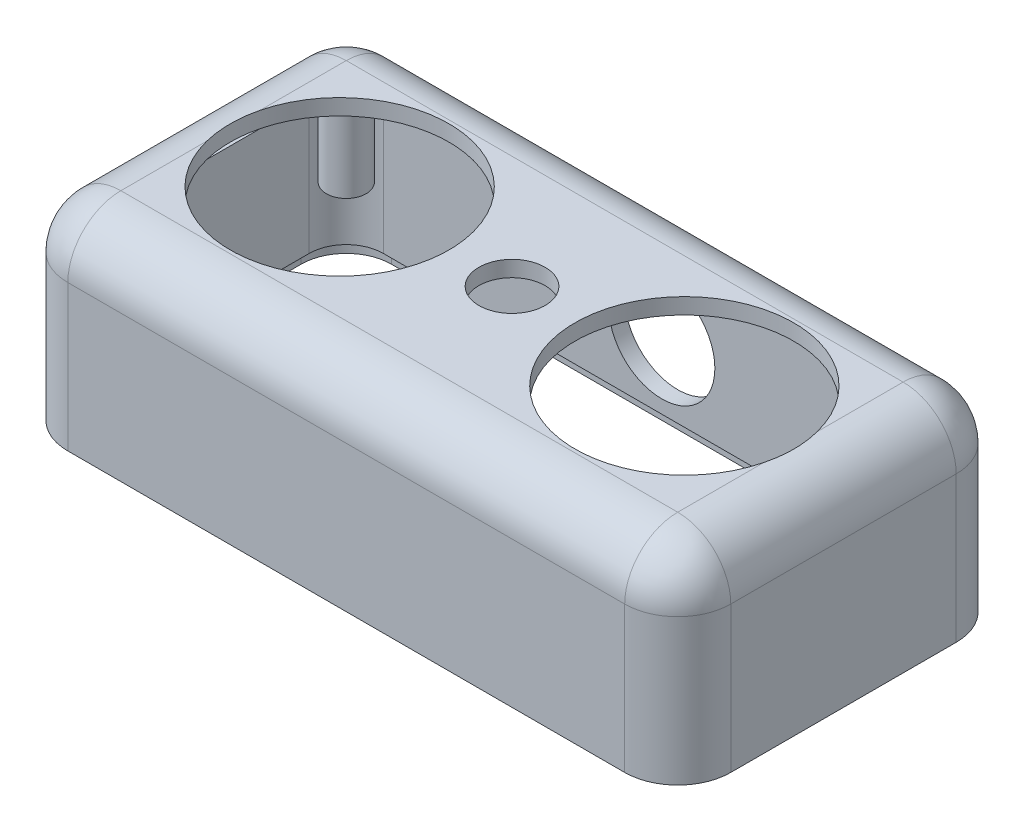
SolidWorks part; units mm, degrees
ref_plane "Front Plane" through (0, 0, 0) normal (0, 0, 1) x (1, 0, 0)
ref_plane "Top Plane" through (0, 0, 0) normal (0, 1, 0) x (1, 0, 0)
ref_plane "Right Plane" through (0, 0, 0) normal (1, 0, 0) x (0, 0, -1)
sketch "Sketch1" plane through (0, 0, 0) normal (0, 1, 0) x (1, 0, 0)
  line L1 (0, 0) -> (50, 0)
  line L2 (0, 0) -> (0, 25)
  line L3 (0, 25) -> (50, 25)
  line L4 (50, 0) -> (50, 25)
  dimension "D1" = 50
  dimension "D2" = 25
extrude "Boss-Extrude2" add sketch "Sketch1" along normal blind 15
fillet "Fillet1" radius 4 4 edges at (50, 7.5, 0) (0, 7.5, 0) (0, 7.5, -25) (50, 7.5, -25)
fillet "Fillet2" radius 4 8 edges at (1.1716, 15, -1.1716) (0, 15, -12.5) (1.1716, 15, -23.8284) (25, 15, -25) (48.8284, 15, -23.8284) (50, 15, -12.5) (48.8284, 15, -1.1716) (25, 15, 0)
shell "Shell1" thickness 1.2
sketch "Sketch2" plane through (0, 13.8, 0) normal (0, -1, 0) x (1, 0, 0)
  line L0 (4, -21) -> (4, -4) construction
  line L1 (38, -12.5) -> (12, -12.5) construction
  line L3 (46, -21) -> (4, -21) construction
  circle A0 centre (38, -12.5) radius 8.25
  circle A1 centre (12, -12.5) radius 8.25
  point P4 (25, -12.5)
  point P9 (4, -12.5)
  point P10 (25, -21)
  dimension "D2" = 16.5
  dimension "D1" = 26
extrude "Cut-Extrude1" cut sketch "Sketch2" against normal through all
sketch "Sketch3" plane through (0, 13.8, 0) normal (0, -1, 0) x (1, 0, 0)
  line L0 (46.25, -21.25) -> (3.75, -21.25) construction
  line L1 (3.75, -21.25) -> (3.75, -3.75) construction
  line L2 (3.75, -3.75) -> (46.25, -3.75) construction
  line L3 (46.25, -3.75) -> (46.25, -21.25) construction
  line L5 (38, -12.5) -> (12, -12.5) construction
  circle A0 centre (46.25, -21.25) radius 1.5
  circle A1 centre (3.75, -21.25) radius 1.5
  circle A2 centre (3.75, -3.75) radius 1.5
  circle A3 centre (46.25, -3.75) radius 1.5
  circle A4 centre (38, -12.5) radius 8.25 construction
  circle A5 centre (38, -12.5) radius 8.25
  circle A6 centre (12, -12.5) radius 8.25 construction
  circle A7 centre (12, -12.5) radius 8.25
  point P14 (25, -21.25)
  point P15 (25, -12.5)
  point P16 (3.75, -12.5)
  dimension "D1" = 3
  dimension "D2" = 42.5
  dimension "D3" = 17.5
extrude "Boss-Extrude3" add sketch "Sketch3" along normal blind 7 contours A1 | A2 | A3 | A0
sketch "Sketch6" plane through (0, 6.8, 0) normal (0, -1, 0) x (1, 0, 0)
  circle A0 centre (46.25, -3.75) radius 0.5
  circle A1 centre (46.25, -21.25) radius 0.5
  circle A2 centre (3.75, -21.25) radius 0.5
  circle A3 centre (3.75, -3.75) radius 0.5
  dimension "D1" = 1
extrude "Cut-Extrude3" cut sketch "Sketch6" against normal blind 3
sketch "Sketch8" plane through (0, 0, 0) normal (0, -1, 0) x (1, 0, 0)
  line L14 (0.6, -4) -> (0.6, -21)
  line L15 (46, -0.6) -> (4, -0.6)
  line L16 (49.4, -21) -> (49.4, -4)
  line L17 (4, -24.4) -> (46, -24.4)
  line L18 (0.6, -4) -> (0.6, -21)
  line L19 (46, -0.6) -> (4, -0.6)
  line L20 (49.4, -21) -> (49.4, -4)
  line L21 (4, -24.4) -> (46, -24.4)
  arc A12 (0.6, -21) -> (4, -24.4) centre (4, -21) ccw
  arc A13 (4, -0.6) -> (0.6, -4) centre (4, -4) ccw
  arc A14 (49.4, -4) -> (46, -0.6) centre (46, -4) ccw
  arc A15 (46, -24.4) -> (49.4, -21) centre (46, -21) ccw
  arc A16 (0.6, -21) -> (4, -24.4) centre (4, -21) ccw
  arc A17 (4, -0.6) -> (0.6, -4) centre (4, -4) ccw
  arc A18 (49.4, -4) -> (46, -0.6) centre (46, -4) ccw
  arc A19 (46, -24.4) -> (49.4, -21) centre (46, -21) ccw
  dimension "D1" = 0.6
extrude "Cut-Extrude6" cut sketch "Sketch8" against normal blind 1
sketch "Sketch9" plane through (0, 0, -25) normal (0, 0, -1) x (-1, 0, 0)
  line L0 (-46, 0) -> (-4, 0) construction
  circle A0 centre (-25, 6) radius 4
  dimension "D1" = 8
  dimension "D2" = 6
extrude "Cut-Extrude15" cut sketch "Sketch9" against normal up to surface (1.2 mm away) up to face at (25, 6, -23.8)
sketch "Sketch13" plane through (0, 13.8, 0) normal (0, -1, 0) x (1, 0, 0)
  circle A0 centre (25, -12.5) radius 2.5
  dimension "D1" = 5
extrude "Cut-Extrude16" cut sketch "Sketch13" against normal through all
